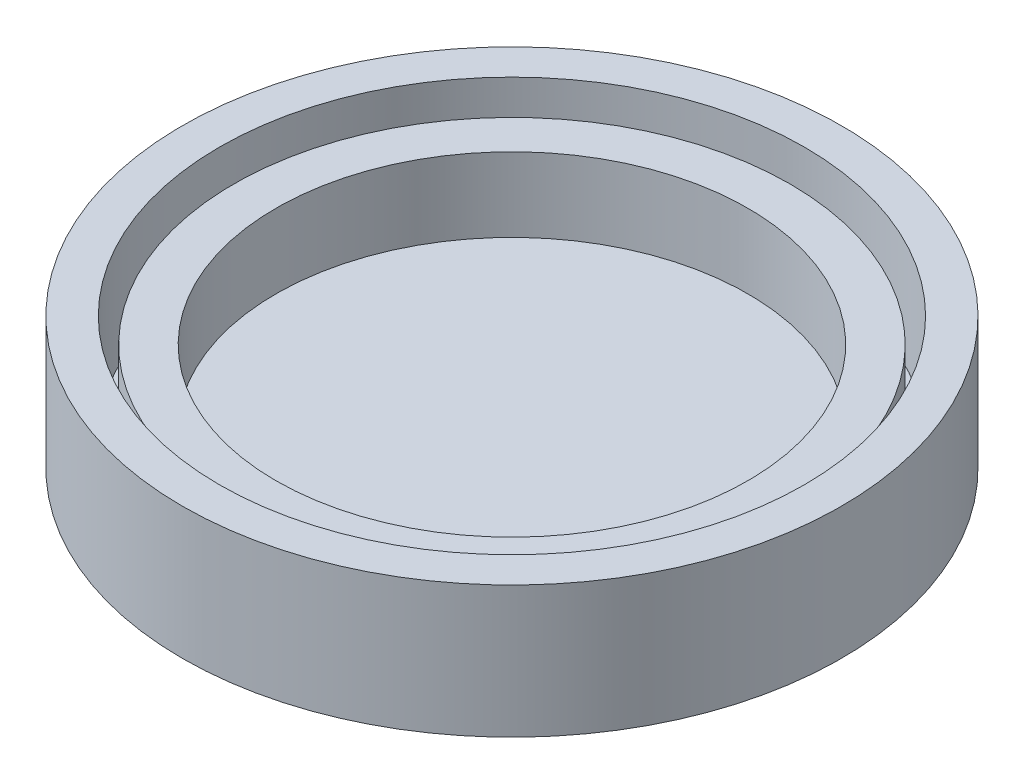
SolidWorks part; units mm, degrees
ref_plane "Front Plane" through (0, 0, 0) normal (0, 0, 1) x (1, 0, 0)
ref_plane "Top Plane" through (0, 0, 0) normal (0, 1, 0) x (1, 0, 0)
ref_plane "Right Plane" through (0, 0, 0) normal (1, 0, 0) x (0, 0, -1)
sketch "Sketch1" plane through (0, 0, 0) normal (0, 1, 0) x (1, 0, 0)
  circle A0 centre (0, 0) radius 40
  dimension "D1" = 80
extrude "Boss-Extrude1" add sketch "Sketch1" along normal blind 13
sketch "Sketch3" plane through (0, 13, 0) normal (0, 1, 0) x (1, 0, 0)
  circle A0 centre (0, 0) radius 35
  dimension "D1" = 70
extrude "Cut-Extrude1" cut sketch "Sketch3" against normal blind 10
sketch "Sketch4" plane through (0, 3, 0) normal (0, 1, 0) x (1, 0, 0)
  circle A0 centre (0, 0) radius 33
  dimension "D1" = 66
extrude "Boss-Extrude2" add sketch "Sketch4" along normal blind 4
sketch "Sketch7" plane through (0, 13, 0) normal (0, 1, 0) x (1, 0, 0)
  circle A0 centre (0, 0) radius 35
  circle A1 centre (0, 0) radius 40
extrude "Boss-Extrude3" add sketch "Sketch7" along normal blind 3
sketch "Sketch8" plane through (0, 16, 0) normal (0, 1, 0) x (1, 0, 0)
  circle A0 centre (0, 0) radius 35.5
  dimension "D1" = 71
extrude "Cut-Extrude2" cut sketch "Sketch8" against normal blind 13
sketch "Sketch9" plane through (0, 3, 0) normal (0, 1, 0) x (1, 0, 0)
  circle A0 centre (0, 0) radius 33.75
  dimension "D1" = 67.5
extrude "Boss-Extrude6" add sketch "Sketch9" along normal blind 7
sketch "Sketch10" plane through (0, 10, 0) normal (0, 1, 0) x (1, 0, 0)
  circle A0 centre (0, 0) radius 28.6455
extrude "Cut-Extrude3" cut sketch "Sketch10" against normal blind 6
sketch "Sketch11" plane through (0, 10, 0) normal (0, 1, 0) x (1, 0, 0)
  circle A0 centre (0, 0) radius 28.6455
  circle A1 centre (0, 0) radius 33.75
extrude "Boss-Extrude8" add sketch "Sketch11" along normal blind 3
